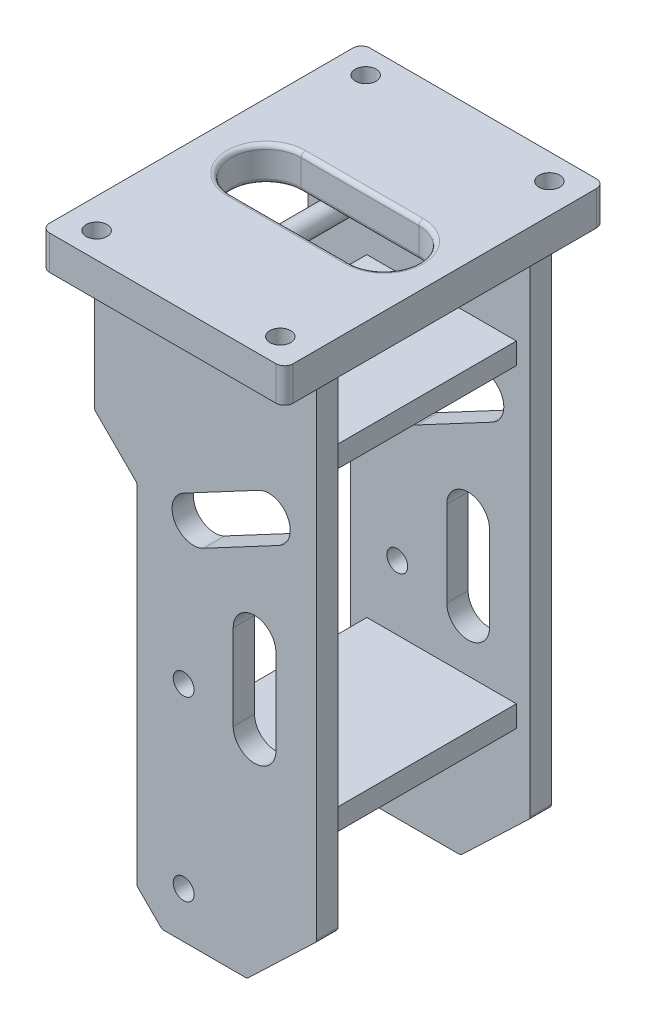
SolidWorks part; units mm, degrees
material "AISI 1020 钢，冷轧"
ref_plane "前视基准面" through (0, 0, 0) normal (0, 0, 1) x (1, 0, 0)
ref_plane "上视基准面" through (0, 0, 0) normal (0, 1, 0) x (1, 0, 0)
ref_plane "右视基准面" through (0, 0, 0) normal (1, 0, 0) x (0, 0, -1)
sketch "草图1" plane through (0, 0, 0) normal (0, 0, 1) x (1, 0, 0)
  line L0 (-46.311, 81.9635) -> (5.689, 81.9635)
  line L1 (5.689, 81.9635) -> (5.689, -32.4971)
  line L3 (-10.5815, -48.0365) -> (-30.4949, -48.0365)
  line L6 (-46.311, 81.9635) -> (-46.311, 49.4145)
  line L7 (-46.311, 49.4145) -> (-36.3585, 39.4849)
  line L16 (-8.8367, 21.4398) -> (-8.8367, 1.4398) construction
  line L17 (-3.8367, 21.4398) -> (-3.8367, 1.4398)
  line L18 (-13.8367, 21.4398) -> (-13.8367, 1.4398)
  line L19 (-23.1383, 38.4738) -> (-5.4837, 47.8714) construction
  line L20 (-25.4877, 42.8874) -> (-7.8331, 52.285)
  line L21 (-20.7889, 34.0601) -> (-3.1343, 43.4577)
  line L22 (-36.3585, 39.4849) -> (-36.3585, -42.1864)
  line L23 (-36.3585, -42.1864) -> (-30.4949, -48.0365)
  line L24 (5.689, -32.4971) -> (-10.5815, -48.0365)
  arc A3 (-3.8367, 21.4398) -> (-13.8367, 21.4398) centre (-8.8367, 21.4398) ccw
  arc A4 (-13.8367, 1.4398) -> (-3.8367, 1.4398) centre (-8.8367, 1.4398) ccw
  arc A6 (-25.4877, 42.8874) -> (-20.7889, 34.0601) centre (-23.1383, 38.4738) ccw
  arc A7 (-3.1343, 43.4577) -> (-7.8331, 52.285) centre (-5.4837, 47.8714) ccw
  circle A8 centre (-25.4316, 4.2386) radius 2.44
  circle A9 centre (-25.4316, -37.2503) radius 2.44
  point P9 (-14.311, 43.1726)
  point P15 (-8.8367, 11.4398)
  dimension "D2" = 10
  dimension "D1" = 130
  dimension "D3" = 20
  dimension "D4" = 20
  dimension "D5" = 10
  dimension "52" = 52
extrude "凸台-拉伸1" add sketch "草图1" along normal blind 5
sketch "草图2" plane through (0, 81.9635, 0) normal (0, 1, 0) x (1, 0, 0)
  line L0 (-20.311, -4.4045) -> (-20.311, -28.7148) construction
  line L1 (-48.811, 60) -> (8.189, 60)
  line L2 (-48.811, 60) -> (-48.811, -15)
  line L3 (-48.811, -15) -> (8.189, -15)
  line L4 (8.189, 60) -> (8.189, -15)
  line L5 (-48.811, 60) -> (8.189, -15) construction
  line L6 (-48.811, -15) -> (8.189, 60) construction
  line L8 (5.689, -5) -> (-46.311, -5) construction
  line L9 (-46.311, 0) -> (5.689, -5) construction
  line L10 (5.689, -5) -> (5.689, 0) construction
  line L11 (5.689, 0) -> (-46.311, -5) construction
  point P0 (-20.311, 22.5)
  point P7 (-20.311, -2.5)
  dimension "D1" = 57
  dimension "D2" = 75
  dimension "D3" = 10
extrude "凸台-拉伸2" add sketch "草图2" along normal blind 8 separate body
sketch "草图3" plane through (0, 89.9635, 0) normal (0, 1, 0) x (1, 0, 0)
  line L0 (-48.811, 22.5) -> (8.189, 22.5)
  line L1 (-48.811, 60) -> (-48.811, -15) construction
  line L2 (8.189, -15) -> (8.189, 60) construction
ref_plane "基准面1" through (0, 0, -22.5) normal (0, 0, 1) x (1, 0, 0)
mirror "镜向2" about plane through (0, 0, -22.5) normal (0, 0, 1) of bodies 101
fillet "圆角2" radius 2 4 edges at (8.189, 85.9635, 15) (8.189, 85.9635, -60) (-48.811, 85.9635, 15) (-48.811, 85.9635, -60)
sketch "草图5" plane through (0, 89.9635, 0) normal (0, 1, 0) x (1, 0, 0)
  line L0 (-48.811, 58) -> (-48.811, -13) construction
  line L1 (6.189, 60) -> (-46.811, 60) construction
  circle A0 centre (-41.811, 54) radius 2.44
  circle A1 centre (1.189, 54) radius 2.44
  circle A2 centre (-41.811, -9) radius 2.44
  circle A3 centre (1.189, -9) radius 2.44
  dimension "D1" = 4.88
  dimension "D2" = 4.88
  dimension "D3" = 4.88
  dimension "D4" = 4.88
  dimension "D5" = 43
  dimension "D6" = 63
  dimension "D7" = 7
  dimension "D8" = 6
extrude "切除-拉伸1" cut sketch "草图5" against normal blind 8
sketch "草图6" plane through (0, 89.9635, 0) normal (0, 1, 0) x (1, 0, 0)
  line L0 (-33.6125, 22.5) -> (-6.0136, 22.5) construction
  line L1 (-48.811, 22.5) -> (8.189, 22.5) construction
  line L2 (-33.6125, 30.6801) -> (-6.0136, 30.6801)
  line L3 (-33.6125, 14.3199) -> (-6.0136, 14.3199)
  arc A0 (-33.6125, 30.6801) -> (-33.6125, 14.3199) centre (-33.6125, 22.5) ccw
  arc A1 (-6.0136, 14.3199) -> (-6.0136, 30.6801) centre (-6.0136, 22.5) ccw
  point P4 (-19.813, 22.5)
extrude "切除-拉伸2" cut sketch "草图6" against normal blind 8
sketch "草图8" plane through (0, 0, 0) normal (0, 0, -1) x (-1, 0, 0)
  line L1 (-2.4624, 62.7147) -> (32.5376, 62.7147)
  line L2 (-2.4624, 62.7147) -> (-2.4624, 57.7147)
  line L3 (-2.4624, 57.7147) -> (32.5376, 57.7147)
  line L4 (32.5376, 62.7147) -> (32.5376, 57.7147)
  line L5 (-2.4624, 62.7147) -> (32.5376, 57.7147) construction
  line L6 (-2.4624, 57.7147) -> (32.5376, 62.7147) construction
  line L7 (-2.4624, -10.8407) -> (32.5376, -10.8407)
  line L8 (-2.4624, -10.8407) -> (-2.4624, -15.8407)
  line L9 (-2.4624, -15.8407) -> (32.5376, -15.8407)
  line L10 (32.5376, -10.8407) -> (32.5376, -15.8407)
  line L11 (-2.4624, -10.8407) -> (32.5376, -15.8407) construction
  line L12 (-2.4624, -15.8407) -> (32.5376, -10.8407) construction
  point P0 (15.0376, 60.2147)
  point P5 (15.0376, -13.3407)
  dimension "D1" = 35
  dimension "D2" = 5
  dimension "D3" = 35
  dimension "D4" = 5
extrude "凸台-拉伸3" add sketch "草图8" along normal up to next separate body
sketch "草图9" plane through (0, 0, 5) normal (0, 0, 1) x (1, 0, 0)
  line L8 (-46.311, 81.9635) -> (-46.311, 49.4145)
  line L9 (-46.311, 49.4145) -> (-36.3585, 39.4849)
  line L10 (-36.3585, 39.4849) -> (-36.3585, -42.1864)
  line L11 (-36.3585, -42.1864) -> (-30.4949, -48.0365)
  line L12 (-30.4949, -48.0365) -> (-10.5815, -48.0365)
  line L13 (-10.5815, -48.0365) -> (5.689, -32.4971)
  line L14 (5.689, -32.4971) -> (5.689, 81.9635)
  line L15 (5.689, 81.9635) -> (-46.311, 81.9635)
  line L16 (-46.311, 81.9635) -> (-46.311, 49.4145)
  line L17 (-46.311, 49.4145) -> (-36.3585, 39.4849)
  line L18 (-36.3585, 39.4849) -> (-36.3585, -42.1864)
  line L19 (-36.3585, -42.1864) -> (-30.4949, -48.0365)
  line L20 (-30.4949, -48.0365) -> (-10.5815, -48.0365)
  line L21 (-10.5815, -48.0365) -> (5.689, -32.4971)
  line L22 (5.689, -32.4971) -> (5.689, 81.9635)
  line L23 (5.689, 81.9635) -> (-46.311, 81.9635)
  dimension "D1" = 0
sketch "草图11" plane through (0, 0, 0) normal (0, 0, -1) x (-1, 0, 0)
  line L0 (46.311, 81.9635) -> (46.311, 49.4145) construction
  line L2 (-5.689, 81.9635) -> (46.311, 81.9635) construction
  circle A0 centre (36.311, 71.9635) radius 2.44
  dimension "D1" = 10
  dimension "D2" = 10
extrude "凸台-拉伸5" add sketch "草图11" along normal up to next and the other way blind 1 separate body
fillet "圆角3" radius 1 8 edges at (2.1665, 81.9635, -22.5) (-41.7926, 81.9635, -22.5) (2.1665, 89.9635, -22.5) (-41.7926, 89.9635, -22.5) (-19.813, 81.9635, -14.3199) (-19.813, 89.9635, -14.3199) (-19.813, 81.9635, -30.6801) (-19.813, 89.9635, -30.6801)
fillet "圆角4" radius 1 8 edges at (5.689, -32.4971, -47.5) (-10.5815, -48.0365, -47.5) (-30.4949, -48.0365, -47.5) (-36.3585, -42.1864, -47.5) (-46.311, 81.9635, -47.5) (-36.3585, 39.4849, -47.5) (-46.311, 49.4145, -47.5) (5.689, 81.9635, -47.5)
fillet "圆角5" radius 1 8 edges at (5.689, 81.9635, 2.5) (5.689, -32.4971, 2.5) (-10.5815, -48.0365, 2.5) (-30.4949, -48.0365, 2.5) (-36.3585, -42.1864, 2.5) (-46.311, 81.9635, 2.5) (-36.3585, 39.4849, 2.5) (-46.311, 49.4145, 2.5)
